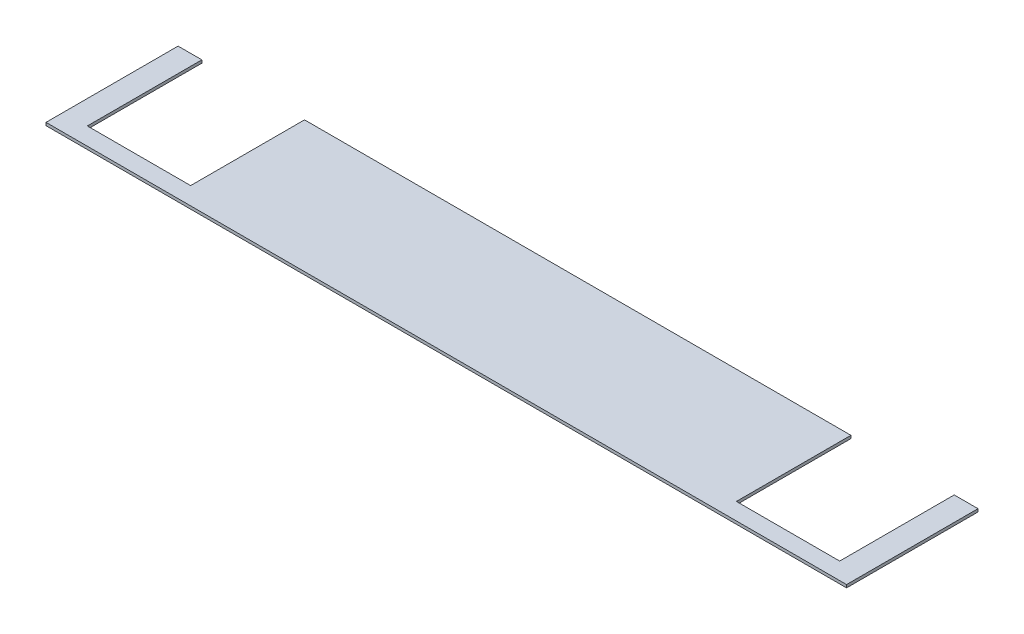
SolidWorks part; units mm, degrees
ref_plane "Front Plane" through (0, 0, 0) normal (0, 0, 1) x (1, 0, 0)
ref_plane "Top Plane" through (0, 0, 0) normal (0, 1, 0) x (1, 0, 0)
ref_plane "Right Plane" through (0, 0, 0) normal (1, 0, 0) x (0, 0, -1)
sketch "Sketch1" plane through (0, 0, 0) normal (0, 1, 0) x (1, 0, 0)
  line L0 (-245.5203, 0) -> (454.4797, 0)
  line L1 (454.4797, 0) -> (454.4797, 114.93)
  line L2 (454.4797, 114.93) -> (433.6797, 114.93)
  line L3 (433.6797, 114.93) -> (433.6797, 14.79)
  line L4 (433.6797, 14.79) -> (343.3597, 14.79)
  line L5 (343.3597, 14.79) -> (343.3597, 114.93)
  line L6 (343.3597, 114.93) -> (-134.4003, 114.93)
  line L7 (-134.4003, 114.93) -> (-134.4003, 15.3512)
  line L8 (-134.4003, 15.3512) -> (-224.7203, 15.3512)
  line L9 (-224.7203, 15.3512) -> (-224.7203, 115.4912)
  line L10 (-224.7203, 115.4912) -> (-245.5203, 115.4912)
  line L11 (-245.5203, 115.4912) -> (-245.5203, 0)
  line L12 (104.4797, 141.1962) -> (104.4797, -47.173) construction
  dimension "D1" = 20.8
  dimension "D2" = 114.93
  dimension "D3" = 14.79
  dimension "D4" = 90.32
  dimension "D5" = 700
extrude "Boss-Extrude1" add sketch "Sketch1" along normal blind 2.54
